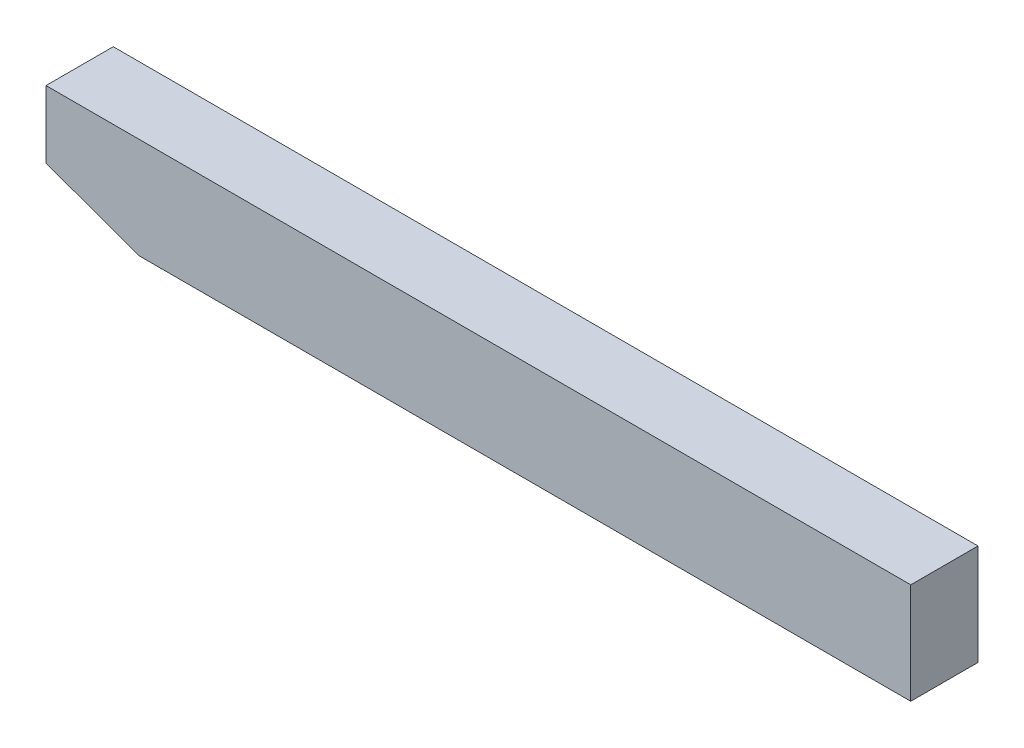
SolidWorks part; units mm, degrees
material "Pine"
ref_plane "X-Y Datum" through (0, 0, 0) normal (0, 0, 1) x (1, 0, 0)
ref_plane "X-Z Datum" through (0, 0, 0) normal (0, 1, 0) x (1, 0, 0)
ref_plane "Y-Z Datum" through (0, 0, 0) normal (1, 0, 0) x (0, 0, -1)
sketch "Sketch1" plane through (0, 0, 0) normal (1, 0, 0) x (0, 0, -1)
  line L1 (-12.7, 12.7) -> (12.7, 12.7)
  line L2 (-12.7, 12.7) -> (-12.7, -12.7)
  line L3 (-12.7, -12.7) -> (12.7, -12.7)
  line L4 (12.7, 12.7) -> (12.7, -12.7)
  line L5 (-12.7, 12.7) -> (12.7, -12.7) construction
  line L6 (-12.7, -12.7) -> (12.7, 12.7) construction
  point P0 (0, 0)
  dimension "D1" = 25.4
extrude "Boss-Extrude1" add sketch "Sketch1" along normal blind 326.5694
sketch "Sketch2" plane through (0, 0, 12.7) normal (0, 0, 1) x (1, 0, 0)
  line L0 (0, -12.7) -> (0, 0)
  line L1 (0, 12.7) -> (0, -12.7) construction
  line L2 (0, 0) -> (35.2949, -12.7)
  line L3 (35.2949, -12.7) -> (0, -12.7)
  line L4 (326.5694, -12.7) -> (0, -12.7) construction
  dimension "D1" = 70.21
  dimension "D2" = 12.7
extrude "Cut-Extrude1" cut sketch "Sketch2" against normal through all both and the other way through all
sketch "Sketch3" plane through (0, 0, 12.7) normal (0, 0, 1) x (1, 0, 0)
  line L0 (326.5694, -12.7) -> (35.2949, -12.7) construction
  line L1 (326.5694, 12.7) -> (0, 12.7)
  line L2 (326.5694, 12.7) -> (326.5694, 25.4)
  line L3 (326.5694, 25.4) -> (0, 25.4)
  line L4 (0, 12.7) -> (0, 25.4)
  line L5 (0, 12.7) -> (0, 0) construction
  dimension "D1" = 38.1
extrude "Boss-Extrude2" add sketch "Sketch3" against normal up to surface (25.4 mm away) up to face at (137.6867, 0, -12.7)
